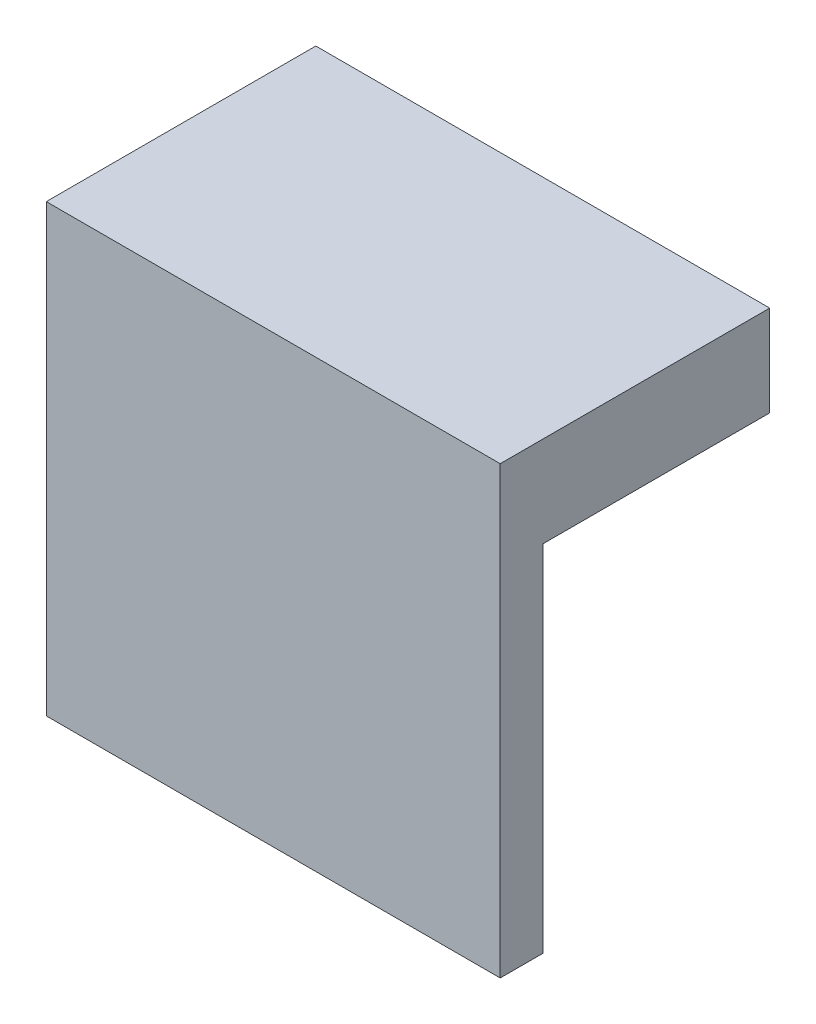
SolidWorks part; units mm, degrees
ref_plane "Front Plane" through (0, 0, 0) normal (0, 0, 1) x (1, 0, 0)
ref_plane "Top Plane" through (0, 0, 0) normal (0, 1, 0) x (1, 0, 0)
ref_plane "Right Plane" through (0, 0, 0) normal (1, 0, 0) x (0, 0, -1)
sketch "Sketch1" plane through (0, 0, 0) normal (0, 1, 0) x (1, 0, 0)
  line L1 (-8, -4.75) -> (8, -4.75)
  line L2 (-8, -4.75) -> (-8, 4.75)
  line L3 (-8, 4.75) -> (8, 4.75)
  line L4 (8, -4.75) -> (8, 4.75)
  line L5 (-8, -4.75) -> (8, 4.75) construction
  line L6 (-8, 4.75) -> (8, -4.75) construction
  point P0 (0, 0)
  dimension "D1" = 9.5
  dimension "D2" = 16
extrude "Boss-Extrude1" add sketch "Sketch1" along normal blind 3.2
sketch "Sketch2" plane through (0, 0, 4.75) normal (0, 0, 1) x (1, 0, 0)
  line L0 (-8, 0) -> (8, 0)
  line L1 (-8, 0) -> (-8, -12.5)
  line L2 (8, 0) -> (8, -12.5)
  line L3 (-8, -12.5) -> (8, -12.5)
  dimension "D1" = 12.5
extrude "Boss-Extrude2" add sketch "Sketch2" against normal blind 1.5
